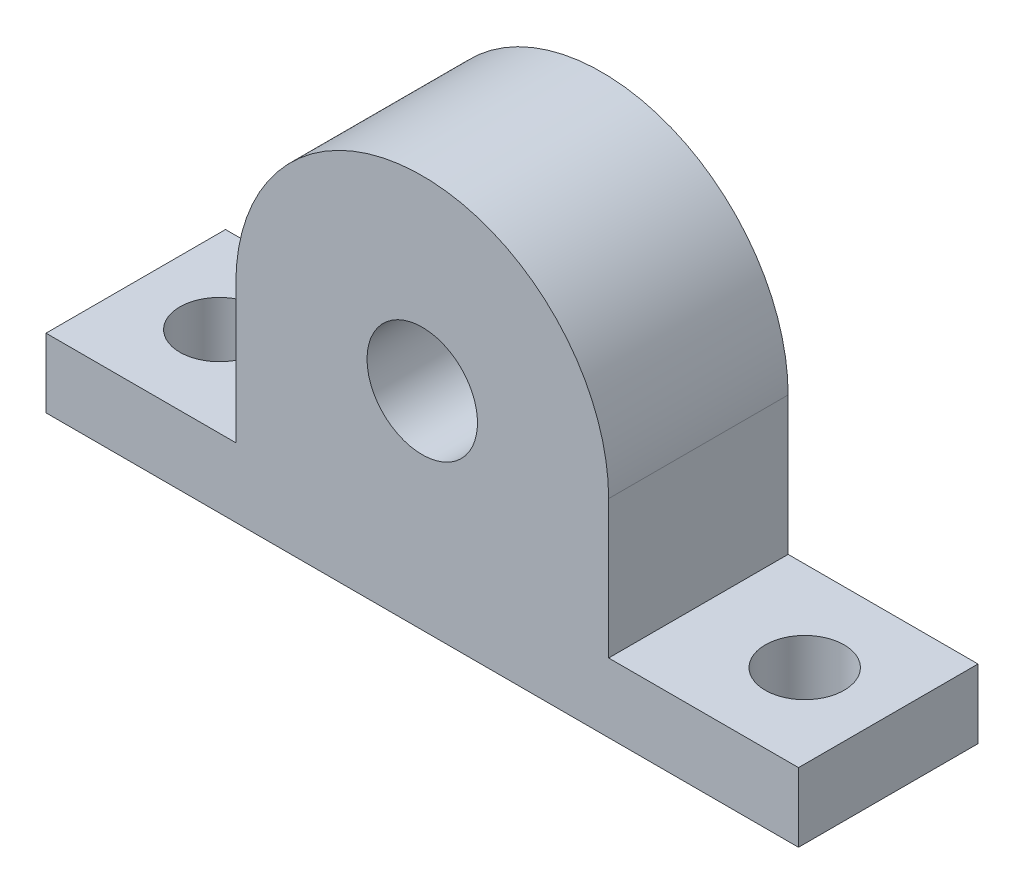
SolidWorks part; units mm, degrees
material "Nickel"
ref_plane "Front Plane" through (0, 0, 0) normal (0, 0, 1) x (1, 0, 0)
ref_plane "Top Plane" through (0, 0, 0) normal (0, 1, 0) x (1, 0, 0)
ref_plane "Right Plane" through (0, 0, 0) normal (1, 0, 0) x (0, 0, -1)
sketch "Sketch1" plane through (0, 0, 0) normal (0, 0, 1) x (1, 0, 0)
  line L1 (0, 0) -> (54.5, 0)
  line L2 (0, 0) -> (0, 5)
  line L3 (0, 5) -> (13.75, 5)
  line L4 (54.5, 0) -> (54.5, 5)
  line L5 (13.75, 15) -> (13.75, 5)
  line L6 (40.75, 15) -> (40.75, 5)
  line L7 (40.75, 5) -> (54.5, 5)
  circle A0 centre (27.25, 15) radius 4
  arc A3 (40.75, 15) -> (13.75, 15) centre (27.25, 15) ccw
  dimension "D3" = 8
  dimension "D1" = 54.5
  dimension "D2" = 15
  dimension "D5" = 5
extrude "Boss-Extrude1" add sketch "Sketch1" along normal blind 13
sketch "Sketch2" plane through (0, 5, 0) normal (0, 1, 0) x (1, 0, 0)
  line L0 (27.25, 0) -> (27.25, -13) construction
  line L1 (40.75, 0) -> (13.75, 0) construction
  line L2 (13.75, -13) -> (40.75, -13) construction
  circle A0 centre (48.45, -6.5) radius 2.8537
  circle A1 centre (6.05, -6.5) radius 2.8537
  dimension "D1" = 21.2
extrude "Cut-Extrude1" cut sketch "Sketch2" against normal blind 13
